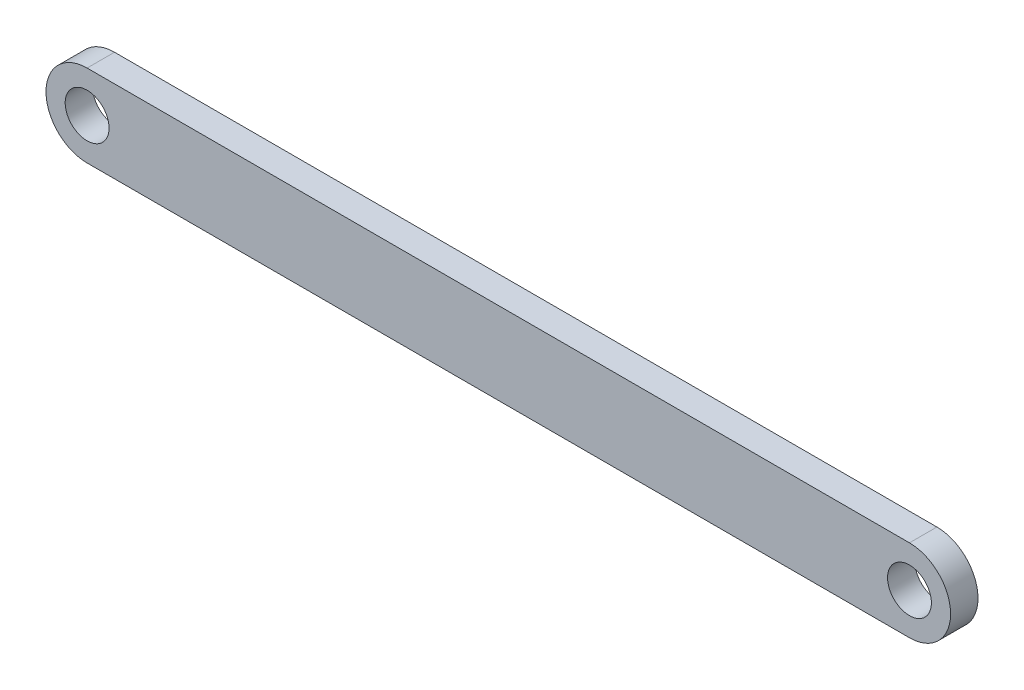
SolidWorks part; units mm, degrees
material "1023 Carbon Steel Sheet (SS)"
ref_plane "Front Plane" through (0, 0, 0) normal (0, 0, 1) x (1, 0, 0)
ref_plane "Top Plane" through (0, 0, 0) normal (0, 1, 0) x (1, 0, 0)
ref_plane "Right Plane" through (0, 0, 0) normal (1, 0, 0) x (0, 0, -1)
sketch "Sketch1" plane through (0, 0, 0) normal (0, 0, 1) x (1, 0, 0)
  line L0 (-75, 0) -> (75, 0) construction
  line L1 (-75, 7.5) -> (75, 7.5)
  line L2 (-75, -7.5) -> (75, -7.5)
  arc A0 (-75, 7.5) -> (-75, -7.5) centre (-75, 0) ccw
  arc A1 (75, -7.5) -> (75, 7.5) centre (75, 0) ccw
  circle A2 centre (75, 0) radius 4
  circle A3 centre (-75, 0) radius 4
  point P3 (0, 0)
  dimension "D3" = 8
  dimension "D1" = 15
  dimension "D2" = 150
extrude "Boss-Extrude1" add sketch "Sketch1" along normal mid plane 5
